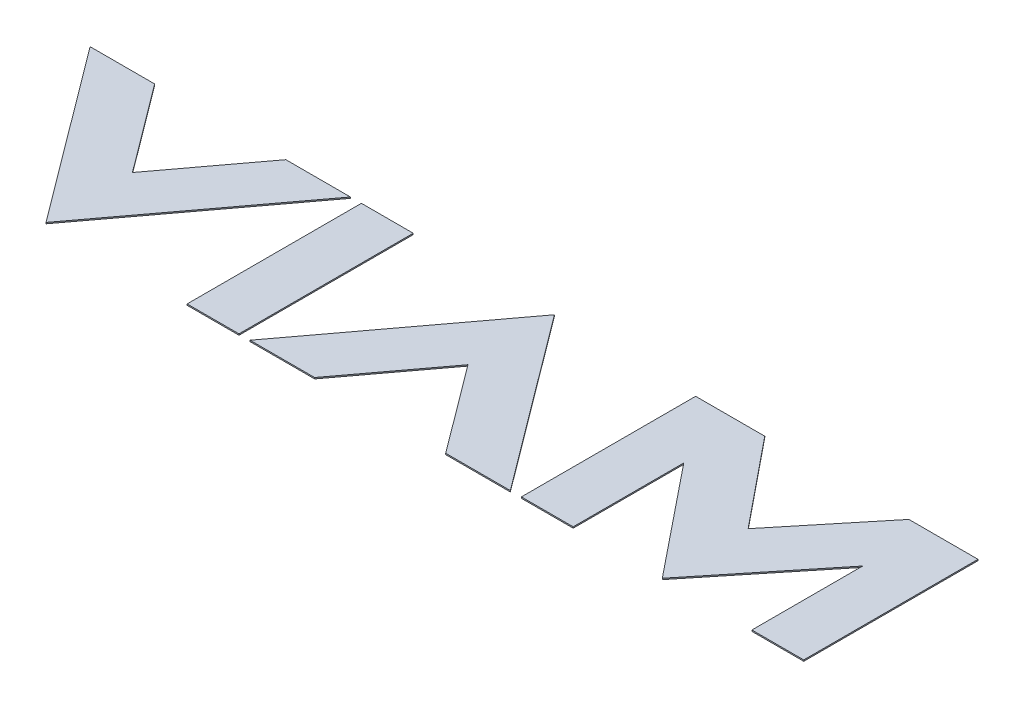
SolidWorks part; units mm, degrees
ref_plane "Front Plane" through (0, 0, 0) normal (0, 0, 1) x (1, 0, 0)
ref_plane "Top Plane" through (0, 0, 0) normal (0, 1, 0) x (1, 0, 0)
ref_plane "Right Plane" through (0, 0, 0) normal (1, 0, 0) x (0, 0, -1)
sketch "Sketch1" plane through (0, 0, 0) normal (0, 1, 0) x (1, 0, 0)
  line L0 (-15, 0) -> (15, 0) construction
  line L1 (-15, 10) -> (15, 10) construction
  line L2 (-15, -10) -> (15, -10) construction
  line L4 (37.5, -12.5) -> (-37.5, -12.5)
  line L5 (37.5, -12.5) -> (37.5, 12.5)
  line L6 (37.5, 12.5) -> (-37.5, 12.5)
  line L7 (-37.5, -12.5) -> (-37.5, 12.5)
  line L8 (37.5, -12.5) -> (-37.5, 12.5) construction
  line L9 (37.5, 12.5) -> (-37.5, -12.5) construction
  arc A0 (-15, 10) -> (-15, -10) centre (-15, 0) ccw construction
  arc A1 (15, -10) -> (15, 10) centre (15, 0) ccw construction
  point P2 (0, 0)
  point P8 (0, 0)
  dimension "D1" = 10
  dimension "D2" = 30
  dimension "D3" = 75
  dimension "D4" = 25
sketch "Sketch2" plane through (-16.7784, 0, 2.9159) normal (0, 1, 0) x (1, 0, 0)
  line L0 (2.563, 10.2) -> (6.7344, 10.2)
  line L1 (6.7344, 10.2) -> (6.7344, -3.8188)
  line L2 (6.7344, -3.8188) -> (2.563, -3.8188)
  line L3 (2.563, -3.8188) -> (2.563, 10.2)
  line L4 (46.612, 10.2) -> (40.7912, 3.0852)
  line L5 (40.7912, 3.0852) -> (35.0159, 10.2)
  line L6 (35.0159, 10.2) -> (29.4555, 10.2)
  line L7 (29.4555, 10.2) -> (29.4555, -3.8188)
  line L8 (29.4555, -3.8188) -> (33.6227, -3.8188)
  line L9 (33.6227, -3.8188) -> (33.6227, 5.0778)
  line L10 (33.6227, 5.0778) -> (40.7912, -3.8188)
  line L11 (40.7912, -3.8188) -> (48.0011, 5.0985)
  line L12 (48.0011, 5.0985) -> (48.0011, -3.8188)
  line L13 (48.0011, -3.8188) -> (52.1724, -3.8188)
  line L14 (52.1724, -3.8188) -> (52.1724, 10.2)
  line L15 (52.1724, 10.2) -> (46.612, 10.2)
  line L16 (-3.5183, 10.2) -> (-8.7934, 3.1348)
  line L17 (-8.7934, 3.1348) -> (-14.0685, 10.2)
  line L18 (-14.0685, 10.2) -> (-19.2651, 10.2)
  line L19 (-19.2651, 10.2) -> (-8.7934, -3.8188)
  line L20 (-8.7934, -3.8188) -> (1.6784, 10.2)
  line L21 (1.6784, 10.2) -> (-3.5183, 10.2)
  line L22 (18.095, 10.2) -> (7.6233, -3.8188)
  line L23 (7.6233, -3.8188) -> (12.8198, -3.8188)
  line L24 (12.8198, -3.8188) -> (18.095, 3.2423)
  line L25 (18.095, 3.2423) -> (23.3701, -3.8229)
  line L26 (23.3701, -3.8229) -> (28.5667, -3.8229)
  line L27 (28.5667, -3.8229) -> (18.095, 10.2)
extrude "Boss-Extrude3" add sketch "Sketch2" along normal blind 0.1
sketch "Sketch3" plane through (0, 0.1, 0) normal (0, 1, 0) x (1, 0, 0)
  line L0 (-61.5, 10.7) -> (61.5, 10.7)
  line L1 (-63.5, -12.7) -> (63.5, -12.7)
  line L2 (-63.5, -12.7) -> (-63.5, 12.7)
  line L3 (-63.5, 12.7) -> (63.5, 12.7)
  line L4 (63.5, -12.7) -> (63.5, 12.7)
  line L5 (-63.5, -12.7) -> (63.5, 12.7) construction
  line L6 (-63.5, 12.7) -> (63.5, -12.7) construction
  line L7 (61.5, -10.7) -> (61.5, 10.7)
  line L8 (-61.5, -10.7) -> (61.5, -10.7)
  line L9 (-61.5, -10.7) -> (-61.5, 10.7)
  point P0 (0, 0)
  dimension "D1" = 25.4
  dimension "D2" = 127
  dimension "D3" = 2
extrude "Boss-Extrude4" [suppressed] add sketch "Sketch3" along normal blind 0.1 separate body
sketch "Sketch5" plane through (0, 0.1, 0) normal (0, 1, 0) x (1, 0, 0)
  line L1 (-36.0434, 7.284) -> (35.3941, 7.284)
  line L2 (-36.0434, 7.284) -> (-36.0434, -6.7347)
  line L3 (-36.0434, -6.7347) -> (35.3941, -6.7347)
  line L4 (35.3941, 7.284) -> (35.3941, -6.7347)
  point P9 (35.3941, 4.6507)
  dimension "D1" = 71.4375
  dimension "D2" = 14.0188
  dimension "D3" = 36.0434
  dimension "D4" = 35.3941
